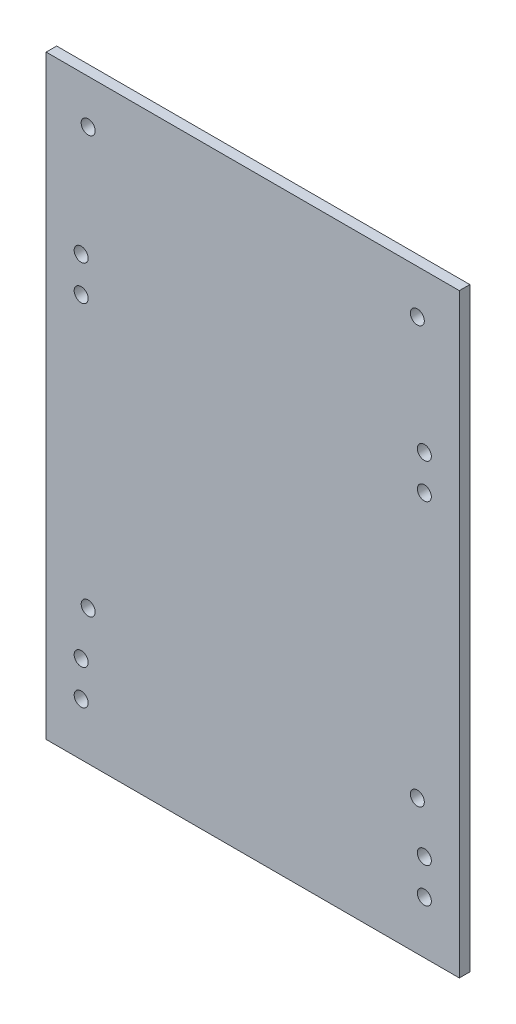
SolidWorks part; units mm, degrees
ref_plane "Front" through (0, 0, 0) normal (0, 0, 1) x (1, 0, 0)
ref_plane "Top" through (0, 0, 0) normal (0, 1, 0) x (1, 0, 0)
ref_plane "Right" through (0, 0, 0) normal (1, 0, 0) x (0, 0, -1)
sketch "草图1" plane through (0, 0, 0) normal (0, 0, 1) x (1, 0, 0)
  line L0 (-143.7233, 0) -> (142.7159, 0) construction
  line L1 (0, 115.509) -> (0, -126.044) construction
  line L2 (-143.7233, 28) -> (142.7159, 28) construction
  line L3 (-59, 100) -> (59, 100)
  line L4 (-59, 100) -> (-59, -70)
  line L5 (-59, -70) -> (59, -70)
  line L6 (59, 100) -> (59, -70)
  circle A0 centre (-49, 55) radius 2
  circle A1 centre (-49, 45) radius 2
  circle A2 centre (49, 45) radius 2
  circle A3 centre (49, 55) radius 2
  circle A4 centre (49, -45) radius 2
  circle A5 centre (49, -55) radius 2
  circle A6 centre (-49, -45) radius 2
  circle A7 centre (-49, -55) radius 2
  circle A8 centre (-47, 87.5) radius 2
  circle A9 centre (47, 87.5) radius 2
  circle A10 centre (47, -31.5) radius 2
  circle A11 centre (-47, -31.5) radius 2
  dimension "D5" = 4
  dimension "D8" = 49
  dimension "D10" = 4
  dimension "D11" = 4
  dimension "D1" = 118
  dimension "D2" = 59
  dimension "D3" = 170
  dimension "D4" = 100
  dimension "D6" = 49
  dimension "D7" = 55
  dimension "D9" = 45
  dimension "D12" = 47
  dimension "D13" = 28
  dimension "D14" = 59.5
extrude "凸台-拉伸1" add sketch "草图1" along normal blind 3
